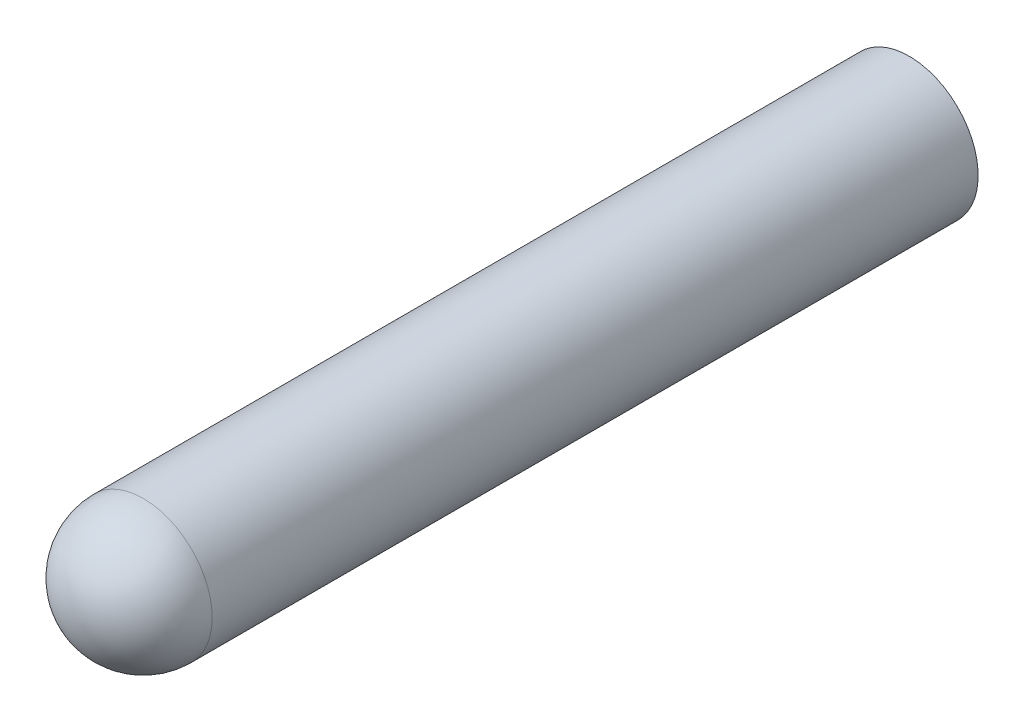
SolidWorks part; units mm, degrees
ref_plane "Alzado" through (0, 0, 0) normal (0, 0, 1) x (1, 0, 0)
ref_plane "Planta" through (0, 0, 0) normal (0, 1, 0) x (1, 0, 0)
ref_plane "Vista lateral" through (0, 0, 0) normal (1, 0, 0) x (0, 0, -1)
sketch "Croquis1" plane through (0, 0, 0) normal (0, 1, 0) x (1, 0, 0)
  line L0 (0, -27.25) -> (0, -25.75)
  line L1 (8.25, -19) -> (8.25, 72.75)
  line L2 (8.25, 72.75) -> (6.75, 72.75)
  line L3 (6.75, 72.75) -> (6.75, -19)
  line L4 (0, -30.3067) -> (0, 174.5502) construction
  arc A1 (0, -25.75) -> (6.75, -19) centre (0, -19) ccw
  arc A2 (0, -27.25) -> (8.25, -19) centre (0, -19) ccw
  dimension "D1" = 100
  dimension "D2" = 8.25
  dimension "D3" = 1.5
  dimension "D4" = 6.75
revolve "Revolución1" add sketch "Croquis1" angle 360 about L4
